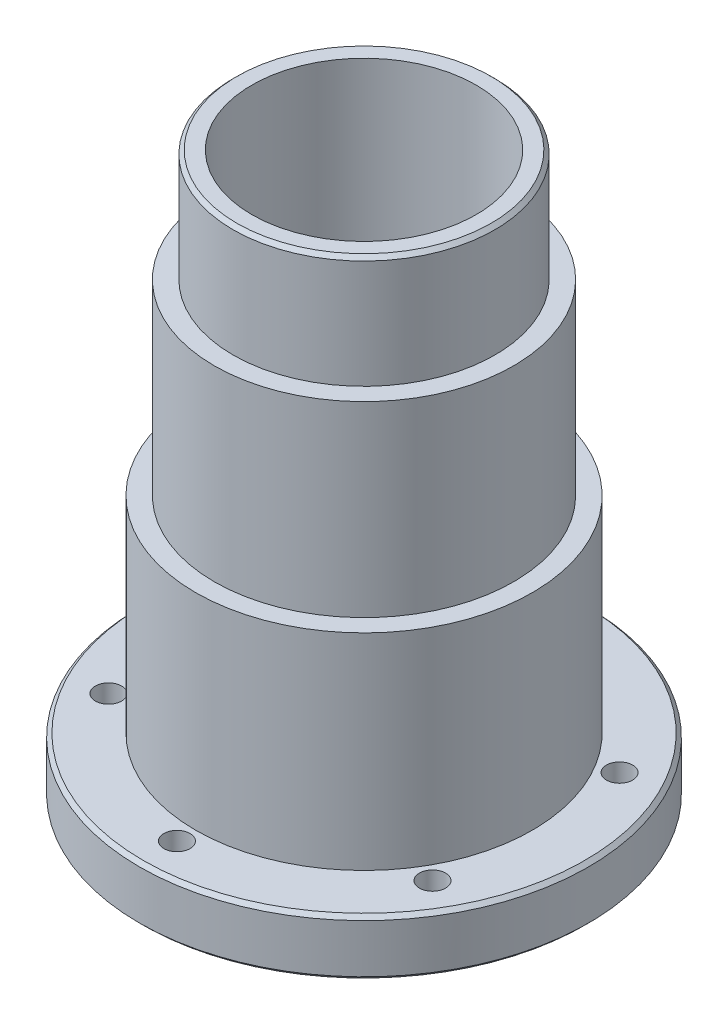
SolidWorks part; units mm, degrees
material "6061 合金"
ref_plane "前视基准面" through (0, 0, 0) normal (0, 0, 1) x (1, 0, 0)
ref_plane "上视基准面" through (0, 0, 0) normal (0, 1, 0) x (1, 0, 0)
ref_plane "右视基准面" through (0, 0, 0) normal (1, 0, 0) x (0, 0, -1)
sketch "草图1" plane through (0, 0, 0) normal (1, 0, 0) x (0, 0, -1)
  line L0 (0, 44) -> (0, 0) construction
  line L1 (-15, 75) -> (-15, 0)
  line L2 (-15, 0) -> (-30, 0)
  line L3 (-30, 0) -> (-30, 7.5)
  line L4 (-30, 7.5) -> (-22.5, 7.5)
  line L5 (-22.5, 7.5) -> (-22.5, 35)
  line L6 (-22.5, 35) -> (-20, 35)
  line L7 (-20, 35) -> (-20, 60)
  line L8 (-20, 60) -> (-17.5, 60)
  line L9 (-17.5, 60) -> (-17.5, 75)
  line L10 (-17.5, 75) -> (-15, 75)
  dimension "D1" = 30
  dimension "D2" = 60
  dimension "D3" = 45
  dimension "D4" = 40
  dimension "D5" = 35
  dimension "D6" = 75
  dimension "D7" = 7.5
  dimension "D8" = 15
  dimension "D9" = 25
revolve "旋转1" add sketch "草图1" angle 360 about L0
hole_wizard "打孔尺寸(%根据)内六角圆柱头螺钉的类型1" positions "草图4" profile "草图5" counterbore size "M3" standard "GB" end condition through all
sketch "草图4" plane through (0, 0, 0) normal (0, -1, 0) x (-1, 0, 0)
  point P0 (0, -25)
  dimension "D1" = 25
sketch "草图5" plane through (0, 0, 25) normal (1, 0, 0) x (0, 0, -1)
  line L0 (0, 0) -> (0, 75)
  line L1 (0, 75) -> (1.75, 75)
  line L3 (1.75, 75) -> (1.75, 4)
  line L4 (1.75, 4) -> (3, 4)
  line L5 (3, 4) -> (3, 0)
  line L7 (3, 0) -> (0, 0)
  line L11 (0, -6.35) -> (0, 107.95) construction
  dimension "通孔孔直径" = 3.5
  dimension "通孔孔深度" = 75
  dimension "柱形沉头孔直径" = 6
  dimension "柱形沉头孔深度" = 4
pattern_circular "阵列(圆周)1" count 6 over 360 about axis through (0, 0, 0) along (0, 1, 0) of "打孔尺寸(%根据)内六角圆柱头螺钉的类型1"
chamfer "倒角1" distance 0.5 angle 45 3 edges at (0, 7.5, 30) (0, 0, 30) (0, 75, 17.5)
